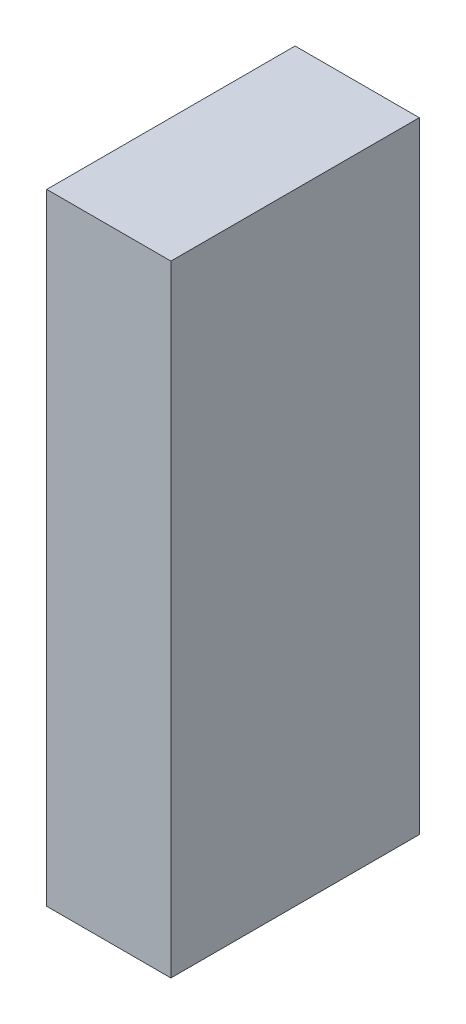
SolidWorks part; units mm, degrees
ref_plane "Front Plane" through (0, 0, 0) normal (0, 0, 1) x (1, 0, 0)
ref_plane "Top Plane" through (0, 0, 0) normal (0, 1, 0) x (1, 0, 0)
ref_plane "Right Plane" through (0, 0, 0) normal (1, 0, 0) x (0, 0, -1)
sketch "Sketch1" plane through (0, 0, 0) normal (0, 1, 0) x (1, 0, 0)
  line L1 (25, -50) -> (-25, -50)
  line L2 (25, -50) -> (25, 50)
  line L3 (25, 50) -> (-25, 50)
  line L4 (-25, -50) -> (-25, 50)
  line L5 (25, -50) -> (-25, 50) construction
  line L6 (25, 50) -> (-25, -50) construction
  point P0 (0, 0)
  dimension "D1" = 50
  dimension "D2" = 100
extrude "Boss-Extrude1" add sketch "Sketch1" along normal blind 250
sketch "Sketch2" plane through (-25, 0, 0) normal (-1, 0, 0) x (0, 0, 1)
  line L0 (50, 250) -> (50, 0) construction
  line L1 (-50, 250) -> (50, 250) construction
  line L2 (38, 225) -> (38, 100) construction
  line L3 (38, 225) -> (-38, 225) construction
  line L4 (-50, 250) -> (-50, 0) construction
  line L5 (-38, 225) -> (-38, 100) construction
  circle A0 centre (38, 225) radius 1.5
  circle A1 centre (38, 100) radius 1.5
  circle A2 centre (-38, 225) radius 1.5
  circle A3 centre (-38, 100) radius 1.5
  dimension "D1" = 12
  dimension "D2" = 25
  dimension "D3" = 3
  dimension "D5" = 3
  dimension "D7" = 3
  dimension "D9" = 3
  dimension "D4" = 125
  dimension "D6" = 12
  dimension "D8" = 125
extrude "Cut-Extrude1" cut sketch "Sketch2" against normal blind 5
sketch "Sketch3" plane through (0, 0, -50) normal (0, 0, -1) x (-1, 0, 0)
  line L0 (25, 250) -> (-0.25, 250) construction
  line L1 (-25, 250) -> (25, 250) construction
  line L2 (-0.25, 250) -> (-0.25, 47) construction
  line L3 (-0.25, 47) -> (-11.25, 47) construction
  circle A0 centre (-0.25, 47) radius 1.5
  circle A1 centre (-11.25, 47) radius 1.5
  dimension "D4" = 3
  dimension "D5" = 3
  dimension "D1" = 25.25
  dimension "D2" = 203
  dimension "D3" = 11
extrude "Cut-Extrude2" cut sketch "Sketch3" against normal blind 5
